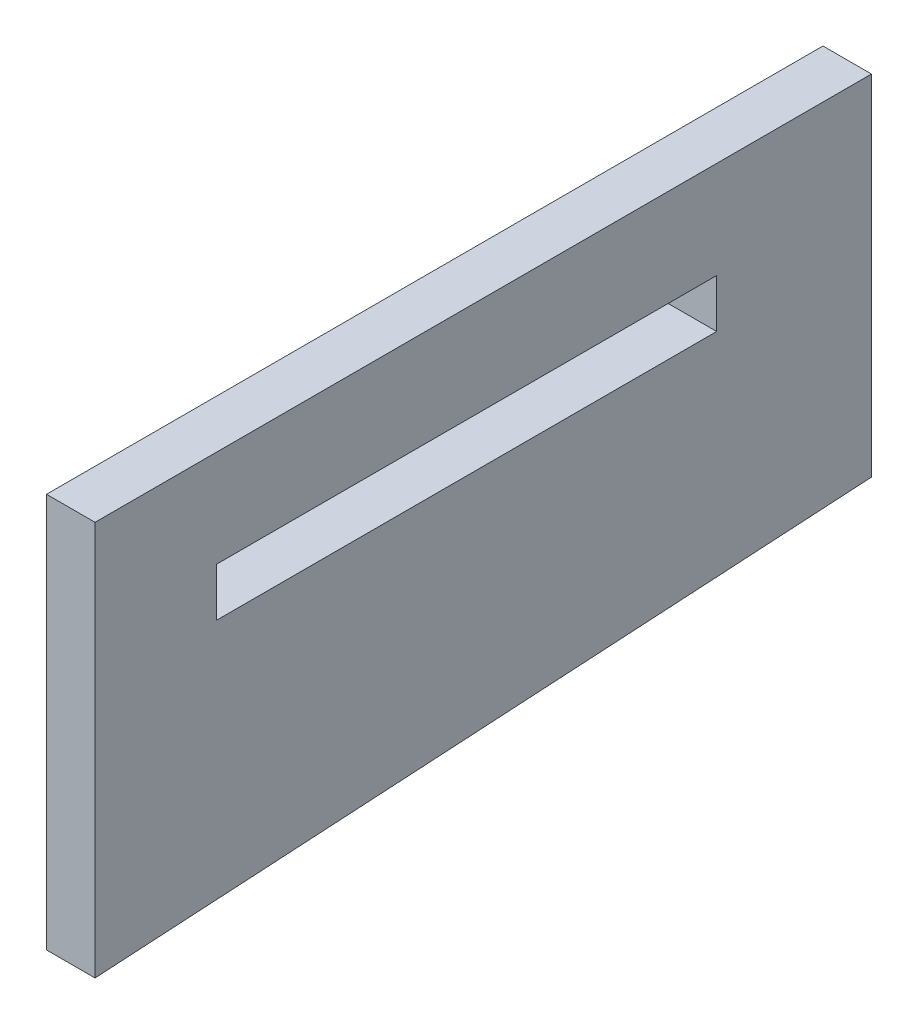
SolidWorks part; units mm, degrees
material "Birch Ply"
ref_plane "Front Plane" through (0, 0, 0) normal (0, 0, 1) x (1, 0, 0)
ref_plane "Top Plane" through (0, 0, 0) normal (0, 1, 0) x (1, 0, 0)
ref_plane "Right Plane" through (0, 0, 0) normal (1, 0, 0) x (0, 0, -1)
sketch "Sketch1" plane through (0, 0, 0) normal (1, 0, 0) x (0, 0, -1)
  line L0 (-40.6727, 9.525) -> (10.1273, 9.525)
  line L1 (10.1273, 9.525) -> (10.1273, -13.3167)
  line L2 (10.1273, -13.3167) -> (-40.6727, -16.296)
  line L3 (-40.6727, -16.296) -> (-40.6727, 9.525)
  line L4 (-16.3676, 3.175) -> (-16.3676, 0) construction
  line L6 (-32.7352, 3.175) -> (0, 3.175) construction
  line L7 (-32.7352, 0) -> (0, 0) construction
  line L8 (-32.7352, 3.175) -> (-32.7352, 0) construction
  line L10 (0, 3.175) -> (0, 0) construction
  line L11 (-32.7352, 3.175) -> (0, 3.175)
  line L12 (-32.7352, 0) -> (0, 0)
  line L13 (-32.7352, 3.175) -> (-32.7352, 0)
  line L14 (0, 3.175) -> (0, 0)
  circle A1 centre (-45.4352, 0) radius 4.7625 construction
  spline S0 degree 3 poles (59.3398, -10.283) (44.2633, -11.2441) (29.1847, -12.1711) (-0.9749, -13.9848) (-16.0559, -14.8713) (-61.3012, -17.4929) (-91.4676, -19.1918) (-121.6352, -20.8698) knots 0 0 0 0 0.25 0.25 0.5 0.5 1 1 1 1 construction
  dimension "D1" = 50.8
  dimension "D2" = 6.35
extrude "Boss-Extrude1" add sketch "Sketch1" against normal blind 3.175
